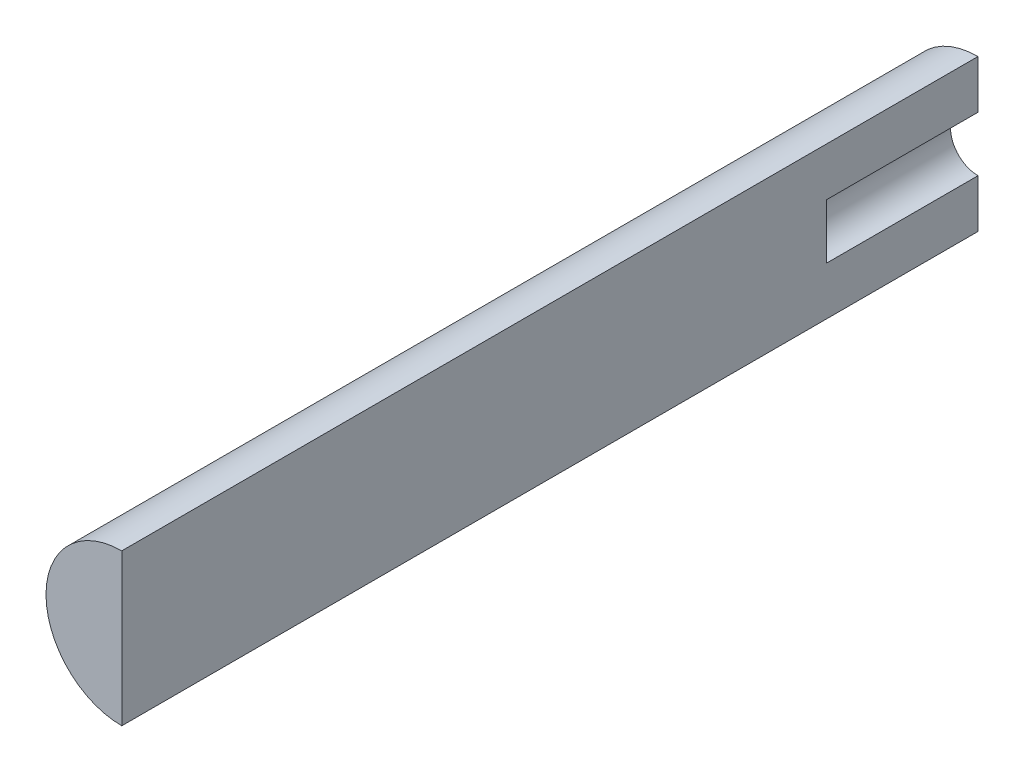
SolidWorks part; units mm, degrees
ref_plane "前视基准面" through (0, 0, 0) normal (0, 0, 1) x (1, 0, 0)
ref_plane "上视基准面" through (0, 0, 0) normal (0, 1, 0) x (1, 0, 0)
ref_plane "右视基准面" through (0, 0, 0) normal (1, 0, 0) x (0, 0, -1)
other "Configuration Table"
sketch "草图1" plane through (0, 0, 0) normal (0, 0, 1) x (1, 0, 0)
  circle A0 centre (0, 0) radius 4
  dimension "D1" = 8
extrude "凸台-拉伸1" add sketch "草图1" along normal blind 45.2
sketch "草图2" plane through (0, 0, 45.2) normal (0, 0, 1) x (1, 0, 0)
  circle A0 centre (0, 0) radius 1.45
  dimension "D1" = 2.9
sketch "草图4" plane through (0, 0, 0) normal (0, 0, -1) x (-1, 0, 0)
  circle A0 centre (0, 0) radius 1.45
  dimension "D1" = 2.9
extrude "切除-拉伸3" cut sketch "草图4" against normal blind 8
sketch "草图5" plane through (0, 0, 0) normal (0, 0, -1) x (-1, 0, 0)
  line L1 (0, -4) -> (0, 4)
  circle A0 centre (0, 0) radius 4 construction
  arc A1 (0, 4) -> (0, -4) centre (0, 0) ccw
extrude "切除-拉伸4" cut sketch "草图5" against normal blind 60
